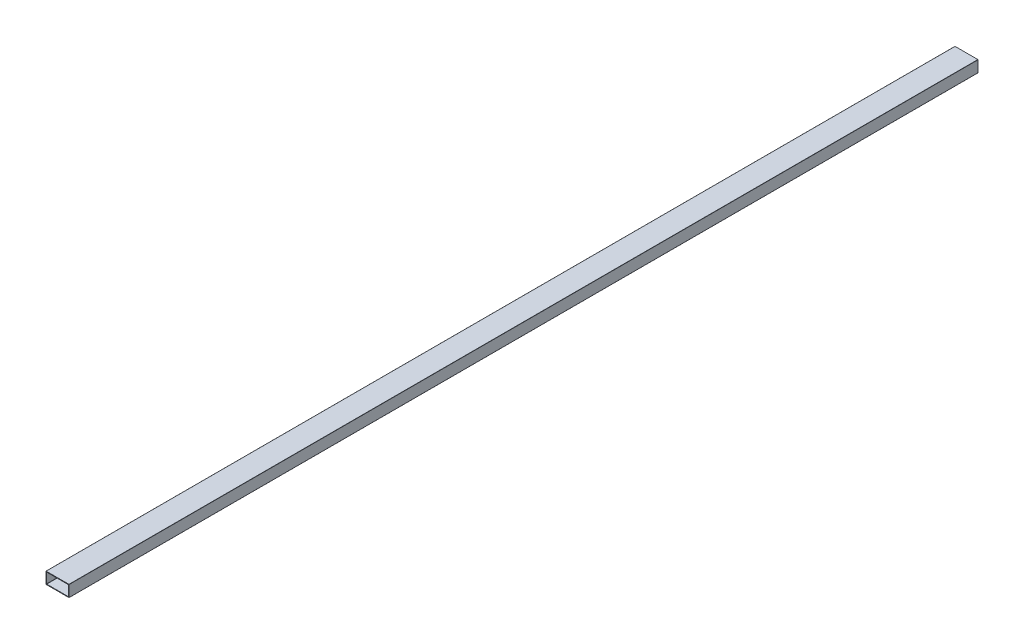
SolidWorks part; units mm, degrees
material "AISI 1035 Acero (SS)"
ref_plane "Alzado" through (0, 0, 0) normal (0, 0, 1) x (1, 0, 0)
ref_plane "Planta" through (0, 0, 0) normal (0, 1, 0) x (1, 0, 0)
ref_plane "Vista lateral" through (0, 0, 0) normal (1, 0, 0) x (0, 0, -1)
sketch "Croquis1" plane through (0, 0, 0) normal (0, 0, 1) x (1, 0, 0)
  line L0 (-72.4, -34.3) -> (-72.4, 34.3)
  line L1 (-76.2, -38.1) -> (76.2, -38.1)
  line L2 (-76.2, -38.1) -> (-76.2, 38.1)
  line L3 (-76.2, 38.1) -> (76.2, 38.1)
  line L4 (76.2, -38.1) -> (76.2, 38.1)
  line L5 (-76.2, -38.1) -> (76.2, 38.1) construction
  line L6 (-76.2, 38.1) -> (76.2, -38.1) construction
  line L7 (-72.4, 34.3) -> (72.4, 34.3)
  line L8 (72.4, -34.3) -> (72.4, 34.3)
  line L9 (-72.4, -34.3) -> (72.4, -34.3)
  point P0 (0, 0)
  dimension "D1" = 76.2
  dimension "D2" = 152.4
  dimension "D3" = 3.8
extrude "Saliente-Extruir1" add sketch "Croquis1" against normal blind 6000
fillet "Redondeo1" radius 1 8 edges at (-72.4, 34.3, -3000) (72.4, 34.3, -3000) (72.4, -34.3, -3000) (-76.2, -38.1, -3000) (-76.2, 38.1, -3000) (-72.4, -34.3, -3000) (76.2, -38.1, -3000) (76.2, 38.1, -3000)
